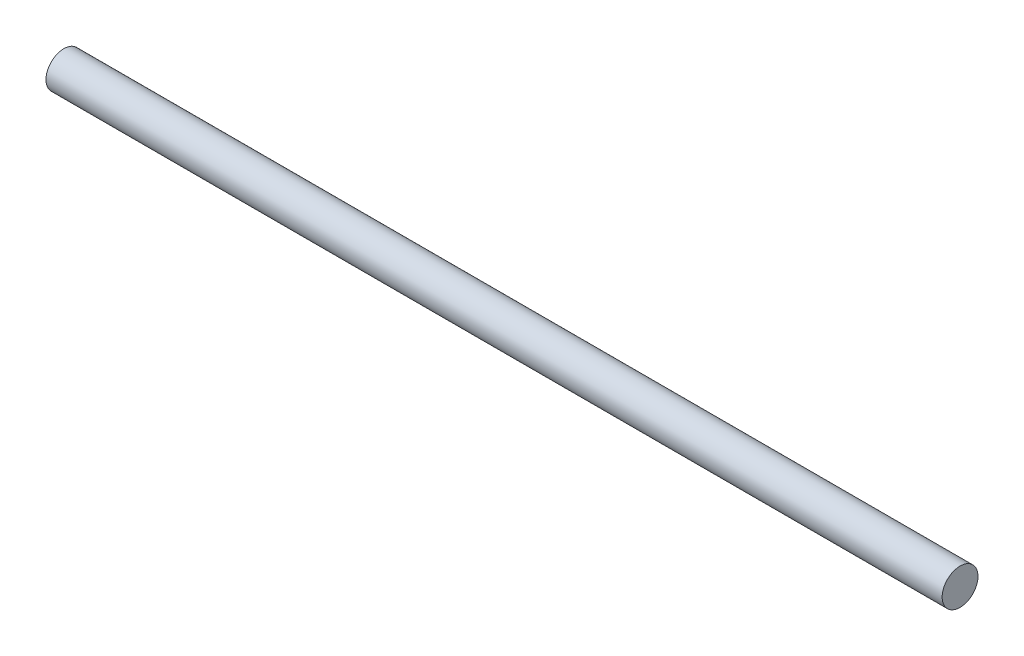
SolidWorks part; units mm, degrees
material "Chrome Stainless Steel"
ref_plane "Front Plane" through (0, 0, 0) normal (0, 0, 1) x (1, 0, 0)
ref_plane "Top Plane" through (0, 0, 0) normal (0, 1, 0) x (1, 0, 0)
ref_plane "Right Plane" through (0, 0, 0) normal (1, 0, 0) x (0, 0, -1)
sketch "Sketch1" plane through (0, 0, 0) normal (1, 0, 0) x (0, 0, -1)
  circle A0 centre (0, 0) radius 6
  dimension "D1" = 12
extrude "Boss-Extrude1" add sketch "Sketch1" along normal blind 300
